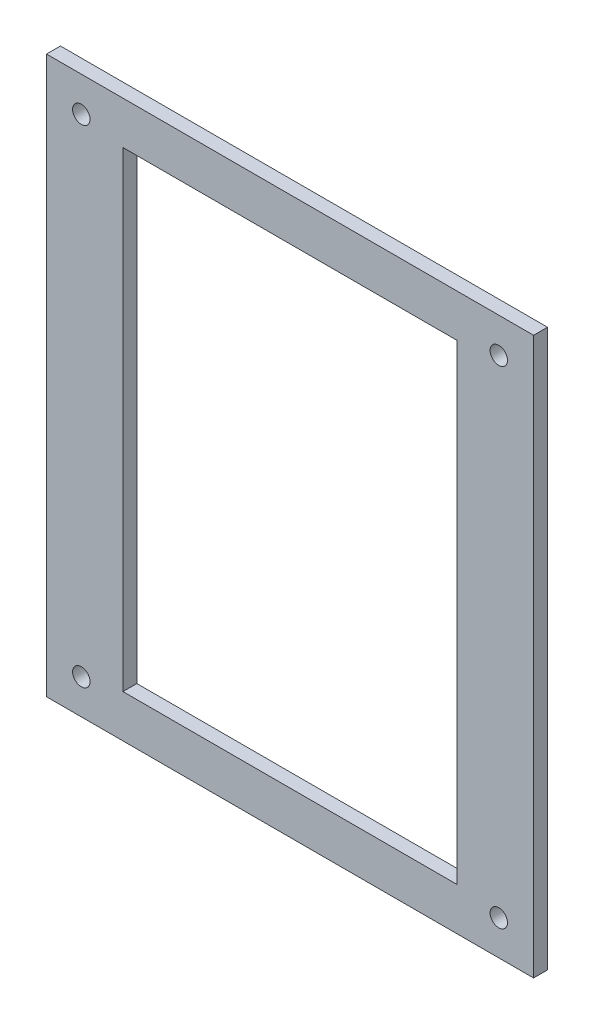
SolidWorks part; units mm, degrees
material "6061 Alloy"
ref_plane "Front Plane" through (0, 0, 0) normal (0, 0, 1) x (1, 0, 0)
ref_plane "Top Plane" through (0, 0, 0) normal (0, 1, 0) x (1, 0, 0)
ref_plane "Right Plane" through (0, 0, 0) normal (1, 0, 0) x (0, 0, -1)
sketch "Sketch1" plane through (0, 0, 0) normal (0, 0, 1) x (1, 0, 0)
  line L0 (82.55, -6.35) -> (6.35, -6.35) construction
  line L1 (0, 0) -> (88.9, 0)
  line L2 (0, 0) -> (0, -101.6)
  line L3 (0, -101.6) -> (88.9, -101.6)
  line L4 (88.9, 0) -> (88.9, -101.6)
  line L5 (13.95, -7.8) -> (74.95, -7.8)
  line L6 (13.95, -7.8) -> (13.95, -93.8)
  line L7 (13.95, -93.8) -> (74.95, -93.8)
  line L8 (74.95, -7.8) -> (74.95, -93.8)
  line L9 (6.35, -6.35) -> (6.35, -95.25) construction
  line L10 (6.35, -95.25) -> (82.55, -95.25) construction
  line L11 (82.55, -95.25) -> (82.55, -6.35) construction
  circle A0 centre (6.35, -6.35) radius 1.59
  circle A1 centre (82.55, -6.35) radius 1.59
  circle A2 centre (6.35, -95.25) radius 1.59
  circle A3 centre (82.55, -95.25) radius 1.59
  point P11 (44.45, 0)
  point P12 (44.45, -7.8)
  point P13 (74.95, -50.8)
  point P14 (88.9, -50.8)
  point P21 (44.45, -6.35)
  point P22 (82.55, -50.8)
  dimension "D7" = 3.18
  dimension "D1" = 61
  dimension "D2" = 86
  dimension "D3" = 76.2
  dimension "D4" = 88.9
  dimension "D5" = 6.35
  dimension "D6" = 6.35
  dimension "D8" = 88.9
  dimension "D9" = 101.6
extrude "Boss-Extrude1" add sketch "Sketch1" along normal blind 2.54
equation "\"D6@Sketch1\"=\"D5@Sketch1\""
equation "\"D3@Sketch1\"=3.0*25.4"
equation "\"D4@Sketch1\"=3.5*25.4"
